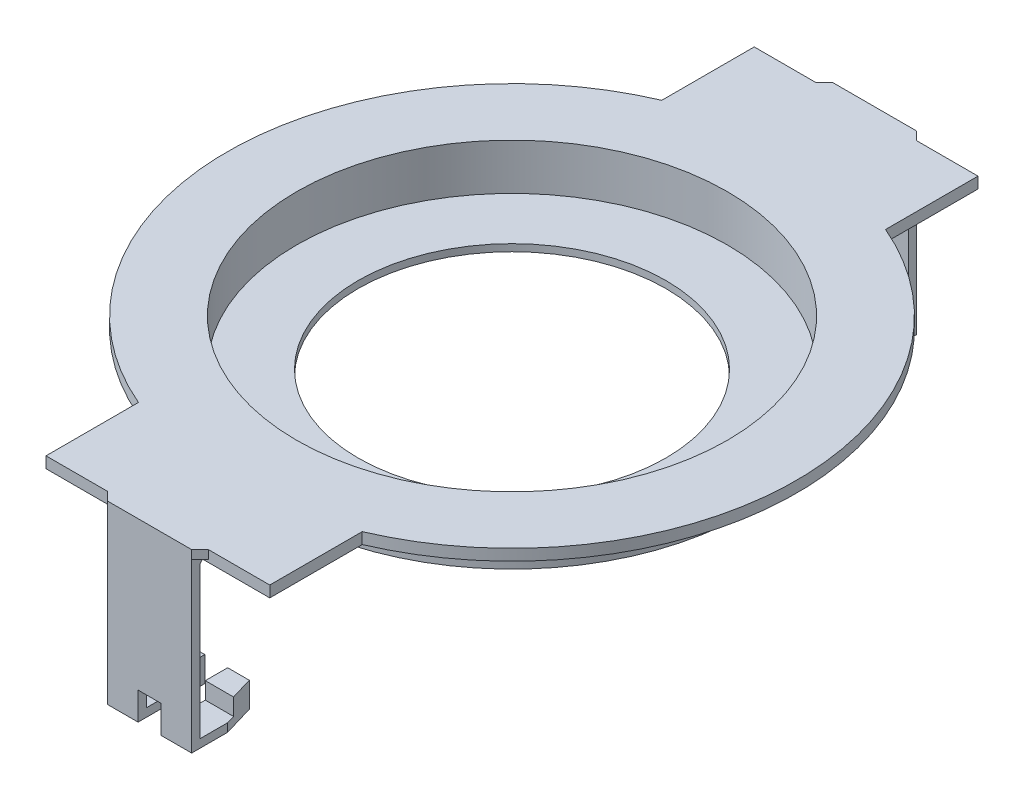
SolidWorks part; units mm, degrees
ref_plane "前基準面" through (0, 0, 0) normal (0, 0, 1) x (1, 0, 0)
ref_plane "上基準面" through (0, 0, 0) normal (0, 1, 0) x (1, 0, 0)
ref_plane "右基準面" through (0, 0, 0) normal (1, 0, 0) x (0, 0, -1)
sketch "草圖1" plane through (0, 0, 0) normal (0, 1, 0) x (1, 0, 0)
  circle A0 centre (0, 0) radius 27.5
  circle A1 centre (0, 0) radius 38.5
extrude "填料-伸長1" add sketch "草圖1" along normal blind 1.25
ref_plane "平面1" through (0, 7.5, 0) normal (0, 1, 0) x (1, 0, 0)
sketch "草圖3" plane through (0, 7.5, 0) normal (0, 1, 0) x (1, 0, 0)
  line L1 (-63.3, 63.3) -> (63.3, 63.3)
  line L2 (-63.3, 63.3) -> (-63.3, -63.3)
  line L3 (-63.3, -63.3) -> (63.3, -63.3)
  line L4 (63.3, 63.3) -> (63.3, -63.3)
  line L5 (-63.3, 63.3) -> (63.3, -63.3) construction
  line L6 (-63.3, -63.3) -> (63.3, 63.3) construction
  circle A0 centre (0, 0) radius 38.5
  point P0 (0, 0)
  dimension "D1" = 126.6
  dimension "D2" = 126.6
extrude "填料-伸長2" add sketch "草圖3" along normal blind 2 separate body
sketch "草圖4" plane through (0, 0, 0) normal (0, -1, 0) x (1, 0, 0)
  circle A0 centre (0, 0) radius 38.5
  circle A1 centre (0, 0) radius 42
extrude "填料-伸長3" add sketch "草圖4" against normal up to next
sketch "草圖5" plane through (0, 0, 63.3) normal (0, 0, 1) x (1, 0, 0)
  line L1 (-63.3, 9.5) -> (63.3, 9.5) construction
  line L3 (-2.04, -22) -> (-2.04, -17.0333)
  line L4 (2.04, -22) -> (2.04, -17.0333)
  line L5 (-2.04, -22) -> (-7.54, -22)
  line L6 (-7.54, -22) -> (-7.54, 9.5)
  line L7 (2.04, -22) -> (7.54, -22)
  line L8 (7.54, -22) -> (7.54, 9.5)
  line L9 (7.54, 9.5) -> (-7.54, 9.5)
  line L10 (-2.04, -17.0333) -> (2.04, -17.0333)
  point P8 (0, -22)
extrude "填料-伸長4" add sketch "草圖5" along normal blind 1.5
sketch "草圖6" plane through (0, 0, 63.3) normal (0, 0, -1) x (-1, 0, 0)
  line L0 (-7.54, -22) -> (-2.04, -22)
  line L1 (-2.04, -22) -> (-2.04, -20.515)
  line L2 (-2.04, -17.0333) -> (-2.04, -22) construction
  line L3 (-2.04, -20.515) -> (-7.54, -20.515)
  line L4 (-7.54, -22) -> (-7.54, 7.5) construction
  line L5 (-7.54, -20.515) -> (-7.54, -22)
  line L6 (2.04, -22) -> (7.54, -22)
  line L7 (7.54, -22) -> (7.54, -20.515)
  line L8 (7.54, 7.5) -> (7.54, -22) construction
  line L9 (7.54, -20.515) -> (2.04, -20.515)
  line L10 (2.04, -22) -> (2.04, -17.0333) construction
  line L11 (2.04, -20.515) -> (2.04, -22)
  dimension "D1" = 1.485
  dimension "D2" = 1.485
extrude "填料-伸長5" add sketch "草圖6" along normal blind 6.43
sketch "草圖7" plane through (0, 0, 56.87) normal (0, 0, -1) x (-1, 0, 0)
  line L0 (-7.54, -22) -> (-7.54, -17.5)
  line L1 (-7.54, -20.515) -> (-7.54, 7.5) construction
  line L2 (-7.54, -17.5) -> (-2.04, -17.5)
  line L3 (-2.04, -17.0333) -> (-2.04, -20.515) construction
  line L4 (-2.04, -17.5) -> (-2.04, -22)
  line L5 (-2.04, -22) -> (-7.54, -22)
  line L6 (2.04, -22) -> (2.04, -17.5)
  line L7 (2.04, -20.515) -> (2.04, -17.0333) construction
  line L8 (2.04, -17.5) -> (7.54, -17.5)
  line L9 (7.54, 7.5) -> (7.54, -20.515) construction
  line L10 (7.54, -17.5) -> (7.54, -22)
  line L11 (7.54, -22) -> (2.04, -22)
extrude "填料-伸長6" add sketch "草圖7" along normal blind 4
sketch "草圖8" plane through (0, 9.5, 0) normal (0, 1, 0) x (1, 0, 0)
  line L0 (0, 63.3) -> (0, 50.8719)
  line L1 (63.3, 63.3) -> (-63.3, 63.3) construction
  line L2 (0, -50.8719) -> (0, -64.8)
  line L3 (7.54, -64.8) -> (-7.54, -64.8) construction
  line L4 (0, -50.8719) -> (20, -50.8719)
  line L5 (0, -50.8719) -> (-20, -50.8719)
  line L6 (-20, -50.8719) -> (-20, -63.3)
  line L7 (-63.3, -63.3) -> (-7.54, -63.3) construction
  line L8 (20, -50.8719) -> (20, -63.3)
  line L9 (7.54, -63.3) -> (63.3, -63.3) construction
  line L10 (-20, -50.8719) -> (-20, -46.7755)
  line L11 (20, -50.8719) -> (20, -46.7755)
  line L12 (-20, -46.7755) -> (-20, 63.3)
  line L13 (-20, 63.3) -> (20, 63.3)
  line L14 (20, 63.3) -> (20, -50.8719)
  line L15 (-63.3, 63.3) -> (-63.3, -63.3)
  line L16 (-63.3, -63.3) -> (63.3, -63.3)
  line L17 (63.3, -63.3) -> (63.3, 63.3)
  line L18 (63.3, 63.3) -> (-63.3, 63.3)
  circle A0 centre (0, 0) radius 50.8719
  line M3 (63.3, -63.3) -> (63.3, 63.3)
  line M4 (63.3, 63.3) -> (-63.3, 63.3)
  line M5 (-63.3, 63.3) -> (-63.3, -63.3)
  line M6 (-63.3, -63.3) -> (-7.54, -63.3)
  line M10 (7.54, -63.3) -> (63.3, -63.3)
extrude "除料-伸長1" cut sketch "草圖8" against normal through all contours A0 L12 L6 L10 M4 M5 M6 | A0 L11 L8 L14 M10 M3 M4
sketch "草圖10" plane through (0, -22, 0) normal (0, -1, 0) x (1, 0, 0)
  line L0 (-7.54, 64.8) -> (-7.54, 58.37)
  line L1 (-7.54, 64.8) -> (-7.54, 52.87) construction
  line L2 (-7.54, 58.37) -> (-6.0283, 52.87)
  line L3 (-2.04, 52.87) -> (-7.54, 52.87) construction
  line L4 (-6.0283, 52.87) -> (-7.54, 52.87)
  line L5 (-7.54, 52.87) -> (-7.54, 58.37)
  line L6 (7.54, 58.37) -> (5.9082, 52.87)
  line L7 (7.54, 64.8) -> (7.54, 52.87) construction
  line L8 (7.54, 52.87) -> (2.04, 52.87) construction
  line L9 (5.9082, 52.87) -> (7.54, 52.87)
  line L10 (7.54, 52.87) -> (7.54, 58.37)
  dimension "D1" = 5.737
extrude "除料-伸長2" cut sketch "草圖10" against normal blind 10 contours L9 L10 L6 | L2 L4 L5
sketch "草圖12" plane through (7.54, 0, 0) normal (1, 0, 0) x (0, 0, -1)
  line L0 (-63.3, 9.5) -> (-63.3, 6.5323)
  line L1 (-63.3, -20.515) -> (-63.3, 7.5) construction
  line L2 (-63.3, 6.5323) -> (-62.5065, 7.5)
  line L3 (55.9591, 7.5) -> (-55.9591, 7.5) construction
  line L4 (-62.5065, 7.5) -> (-63.3, 7.5)
  line M4 (-63.3, -20.515) -> (-63.3, 7.5)
extrude "填料-伸長7" add sketch "草圖12" against normal blind 15.08 contours L2 L4 M4
sketch "草圖14" plane through (0, 9.5, 0) normal (0, 1, 0) x (1, 0, 0)
  line L0 (-7.54, -64.8) -> (-9.04, -63.3)
  line L1 (-20, -63.3) -> (-7.54, -63.3) construction
  line L2 (-9.04, -63.3) -> (-7.54, -63.3)
  line L3 (-7.54, -63.3) -> (-7.54, -64.8)
  line L4 (7.54, -64.8) -> (7.54, -63.3)
  line L5 (7.54, -64.8) -> (9.04, -63.3)
  line L6 (7.54, -63.3) -> (20, -63.3) construction
  line L7 (9.04, -63.3) -> (7.54, -63.3)
extrude "填料-伸長8" add sketch "草圖14" against normal blind 1.5
sketch "草圖16" plane through (0, 0, -63.3) normal (0, 0, -1) x (-1, 0, 0)
  line L0 (0, 9.5) -> (-7.54, 9.5)
  line L1 (-20, 9.5) -> (20, 9.5) construction
  line L2 (0, 9.5) -> (7.54, 9.5)
  line L3 (-7.54, 9.5) -> (-7.54, -22)
  line L4 (-7.54, -22) -> (-2.04, -22)
  line L5 (-2.04, -22) -> (-2.04, -17.0333)
  line L6 (-2.04, -17.0333) -> (2.04, -17.0333)
  line L7 (2.04, -17.0333) -> (2.04, -22)
  line L8 (2.04, -22) -> (7.54, -22)
  line L9 (7.54, -22) -> (7.54, 9.5)
extrude "填料-伸長9" add sketch "草圖16" along normal blind 1.5
sketch "草圖17" plane through (0, 0, -63.3) normal (0, 0, 1) x (1, 0, 0)
  line L0 (-7.54, -22) -> (-7.54, -20.5)
  line L1 (-7.54, 8) -> (-7.54, -22) construction
  line L2 (-7.54, -20.5) -> (-2.04, -20.515)
  line L3 (-2.04, -20.515) -> (-2.04, -22)
  line L4 (-2.04, -22) -> (-7.54, -22)
  line L5 (2.04, -20.515) -> (7.54, -20.515)
  line L6 (7.54, -20.515) -> (7.54, -22)
  line L7 (7.54, -22) -> (2.04, -22)
  line L8 (2.04, -22) -> (2.04, -20.515)
extrude "填料-伸長10" add sketch "草圖17" along normal blind 6.43
sketch "草圖18" plane through (0, -22, 0) normal (0, -1, 0) x (1, 0, 0)
  line L0 (-2.04, -56.87) -> (-2.04, -52.87)
  line L1 (-2.04, -56.87) -> (-7.54, -56.87)
  line L2 (-7.54, -56.87) -> (-7.54, -52.87)
  line L3 (-7.54, -52.87) -> (-2.04, -52.87)
  line L4 (2.04, -56.87) -> (2.04, -52.87)
  line L5 (2.04, -56.87) -> (7.54, -56.87)
  line L6 (7.54, -56.87) -> (7.54, -52.87)
  line L7 (7.54, -52.87) -> (2.04, -52.87)
extrude "填料-伸長12" add sketch "草圖18" against normal blind 4.5
sketch "草圖19" plane through (0, -22, 0) normal (0, -1, 0) x (1, 0, 0)
  line L0 (-7.54, -64.8) -> (-7.54, -58.37)
  line L1 (-7.54, -64.8) -> (-7.54, -52.87) construction
  line L2 (-7.54, -58.37) -> (-6.0101, -52.87)
  line L3 (-2.04, -52.87) -> (-7.54, -52.87) construction
  line L4 (7.54, -64.8) -> (7.54, -58.37)
  line L5 (7.54, -64.8) -> (7.54, -52.87) construction
  line L6 (7.54, -58.37) -> (6.0194, -52.87)
  line L7 (7.54, -52.87) -> (2.04, -52.87) construction
  line L8 (6.0194, -52.87) -> (7.54, -52.87)
  line L9 (7.54, -52.87) -> (7.54, -58.37)
  line L10 (-7.54, -58.37) -> (-7.54, -52.87)
  line L11 (-7.54, -52.87) -> (-6.0101, -52.87)
  line M3 (-2.04, -52.87) -> (-7.54, -52.87)
  line M4 (-7.54, -52.87) -> (-7.54, -64.8)
extrude "除料-伸長3" cut sketch "草圖19" against normal blind 7 contours L2 M4 M3 | L9 L8 L6
sketch "草圖21" plane through (0, 9.5, 0) normal (0, 1, 0) x (1, 0, 0)
  line L0 (-7.54, 64.8) -> (-9.04, 63.3)
  line L1 (-7.54, 63.3) -> (-20, 63.3) construction
  line L2 (-9.04, 63.3) -> (-7.54, 63.3)
  line L3 (-7.54, 63.3) -> (-7.54, 64.8)
  line L4 (7.54, 64.8) -> (9.04, 63.3)
  line L5 (20, 63.3) -> (7.54, 63.3) construction
  line L6 (9.04, 63.3) -> (7.54, 63.3)
  line L7 (7.54, 63.3) -> (7.54, 64.8)
extrude "填料-伸長13" add sketch "草圖21" against normal blind 1.5
sketch "草圖23" plane through (-7.54, 0, 0) normal (-1, 0, 0) x (0, 0, 1)
  line L0 (-63.3, 9.5) -> (-63.3, 7.5)
  line L1 (55.9591, 7.5) -> (-55.9591, 7.5) construction
  line L2 (-63.3, 7.5) -> (-63.3, 6.53)
  line L3 (-63.3, -20.5) -> (-63.3, 7.5) construction
  line L4 (-63.3, 6.53) -> (-62.5219, 7.5)
  line L5 (-62.5219, 7.5) -> (-63.3, 7.5)
  line M8 (-63.3, -20.5) -> (-63.3, 7.5)
extrude "填料-伸長14" add sketch "草圖23" against normal blind 15.08 contours L4 L5 M8
